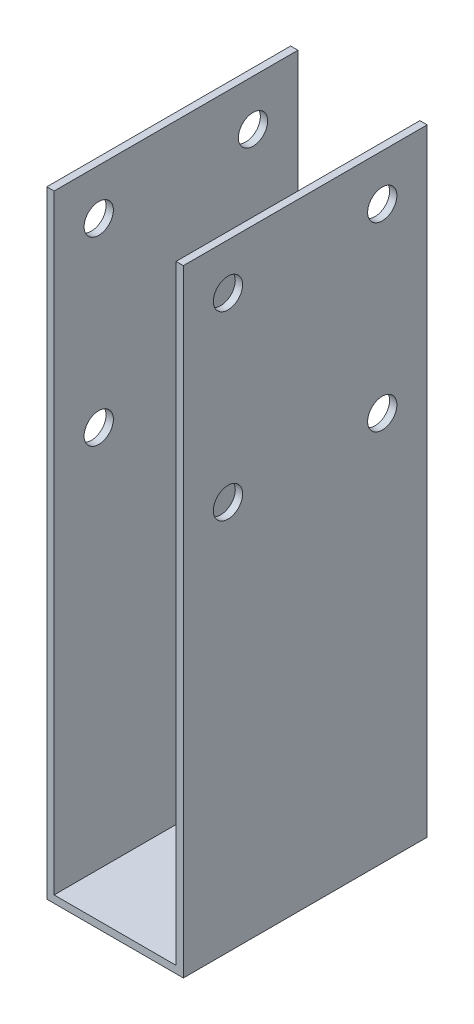
SolidWorks part; units mm, degrees
ref_plane "Alzado" through (0, 0, 0) normal (0, 0, 1) x (1, 0, 0)
ref_plane "Planta" through (0, 0, 0) normal (0, 1, 0) x (1, 0, 0)
ref_plane "Vista lateral" through (0, 0, 0) normal (1, 0, 0) x (0, 0, -1)
sketch "Croquis1" plane through (0, 0, 0) normal (0, 0, 1) x (1, 0, 0)
  line L0 (-28, 125) -> (-28, -128)
  line L1 (-28, -128) -> (28, -128)
  line L2 (-25, 125) -> (-25, -125)
  line L3 (-25, -125) -> (25, -125)
  line L4 (25, 125) -> (25, -125)
  line L5 (-25, 125) -> (25, -125) construction
  line L6 (-25, -125) -> (25, 125) construction
  line L7 (28, 125) -> (28, -128)
  line L8 (-25, 125) -> (-28, 125)
  line L9 (25, 125) -> (28, 125)
  point P0 (0, 0)
  dimension "D1" = 250
  dimension "D2" = 50
  dimension "D3" = 3
extrude "Saliente-Extruir1" add sketch "Croquis1" along normal blind 100
sketch "Croquis2" plane through (28, 0, 0) normal (1, 0, 0) x (0, 0, -1)
  circle A0 centre (-81.7042, 106.1157) radius 6
  circle A1 centre (-18.4341, 106.1157) radius 6
  circle A2 centre (-18.4341, 31.8284) radius 6
  circle A3 centre (-81.7042, 31.8284) radius 6
extrude "Cortar-Extruir1" cut sketch "Croquis2" against normal through all
